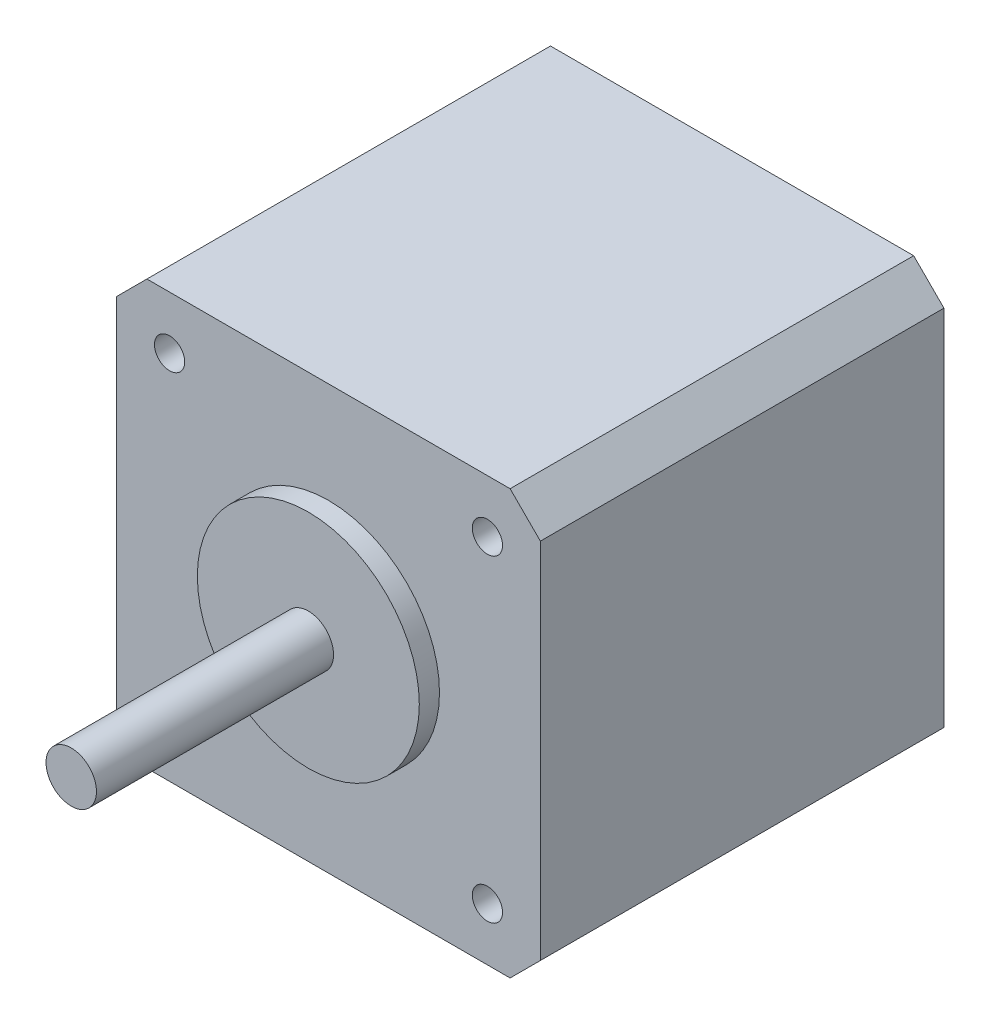
SolidWorks part; units mm, degrees
ref_plane "Front Plane" through (0, 0, 0) normal (0, 0, 1) x (1, 0, 0)
ref_plane "Top Plane" through (0, 0, 0) normal (0, 1, 0) x (1, 0, 0)
ref_plane "Right Plane" through (0, 0, 0) normal (1, 0, 0) x (0, 0, -1)
sketch "Sketch1" plane through (0, 0, 0) normal (0, 0, 1) x (1, 0, 0)
  line L1 (-21, 21) -> (21, 21)
  line L2 (-21, 21) -> (-21, -21)
  line L3 (-21, -21) -> (21, -21)
  line L4 (21, 21) -> (21, -21)
  line L5 (-21, 21) -> (21, -21) construction
  line L6 (-21, -21) -> (21, 21) construction
  point P0 (0, 0)
  dimension "D1" = 42
  dimension "D2" = 42
extrude "Boss-Extrude1" add sketch "Sketch1" along normal blind 40
sketch "Sketch2" plane through (0, 0, 40) normal (0, 0, 1) x (1, 0, 0)
  circle A0 centre (0, 0) radius 11
extrude "Boss-Extrude2" add sketch "Sketch2" along normal blind 2
sketch "Sketch3" plane through (0, 0, 42) normal (0, 0, 1) x (1, 0, 0)
  circle A0 centre (0, 0) radius 2.5
extrude "Boss-Extrude3" add sketch "Sketch3" along normal blind 23.5
chamfer "Chamfer1" distance 3 angle 45 4 edges at (-21, -21, 20) (21, -21, 20) (21, 21, 20) (-21, 21, 20)
sketch "Sketch4" plane through (0, 0, 40) normal (0, 0, 1) x (1, 0, 0)
  line L1 (-15.75, -15.75) -> (15.75, -15.75) construction
  line L2 (-15.75, -15.75) -> (-15.75, 15.75) construction
  line L3 (-15.75, 15.75) -> (15.75, 15.75) construction
  line L4 (15.75, -15.75) -> (15.75, 15.75) construction
  line L5 (-15.75, -15.75) -> (15.75, 15.75) construction
  line L6 (-15.75, 15.75) -> (15.75, -15.75) construction
  circle A0 centre (-15.75, 15.75) radius 1.5
  circle A1 centre (15.75, 15.75) radius 1.5
  circle A2 centre (-15.75, -15.75) radius 1.5
  circle A3 centre (15.75, -15.75) radius 1.5
  point P0 (0, 0)
  dimension "D1" = 31.5
  dimension "D2" = 31.5
extrude "Cut-Extrude1" cut sketch "Sketch4" against normal blind 10
